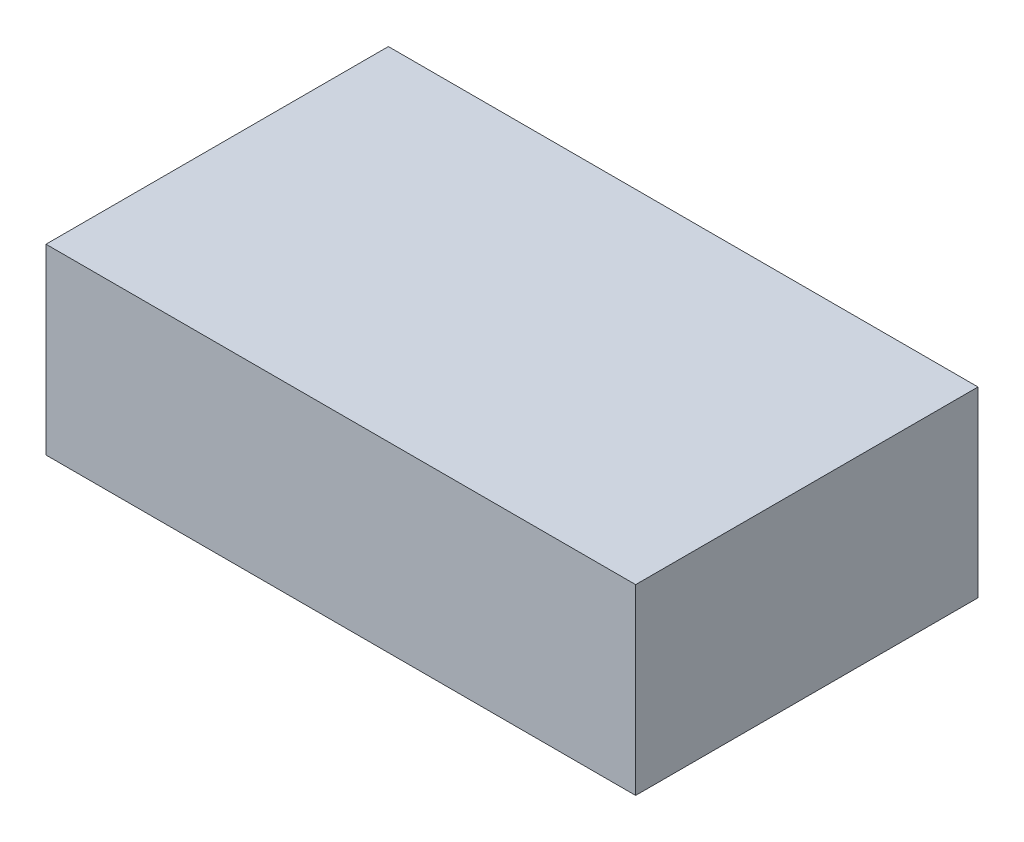
SolidWorks part; units mm, degrees
ref_plane "정면" through (0, 0, 0) normal (0, 0, 1) x (1, 0, 0)
ref_plane "윗면" through (0, 0, 0) normal (0, 1, 0) x (1, 0, 0)
ref_plane "우측면" through (0, 0, 0) normal (1, 0, 0) x (0, 0, -1)
sketch "스케치1" plane through (0, 0, 0) normal (0, 1, 0) x (1, 0, 0)
  line L1 (0, 0) -> (46.5, 0)
  line L2 (0, 0) -> (0, 27)
  line L3 (0, 27) -> (46.5, 27)
  line L4 (46.5, 0) -> (46.5, 27)
  dimension "D1" = 46.5
  dimension "D2" = 27
extrude "보스-돌출1" add sketch "스케치1" along normal blind 14.4
